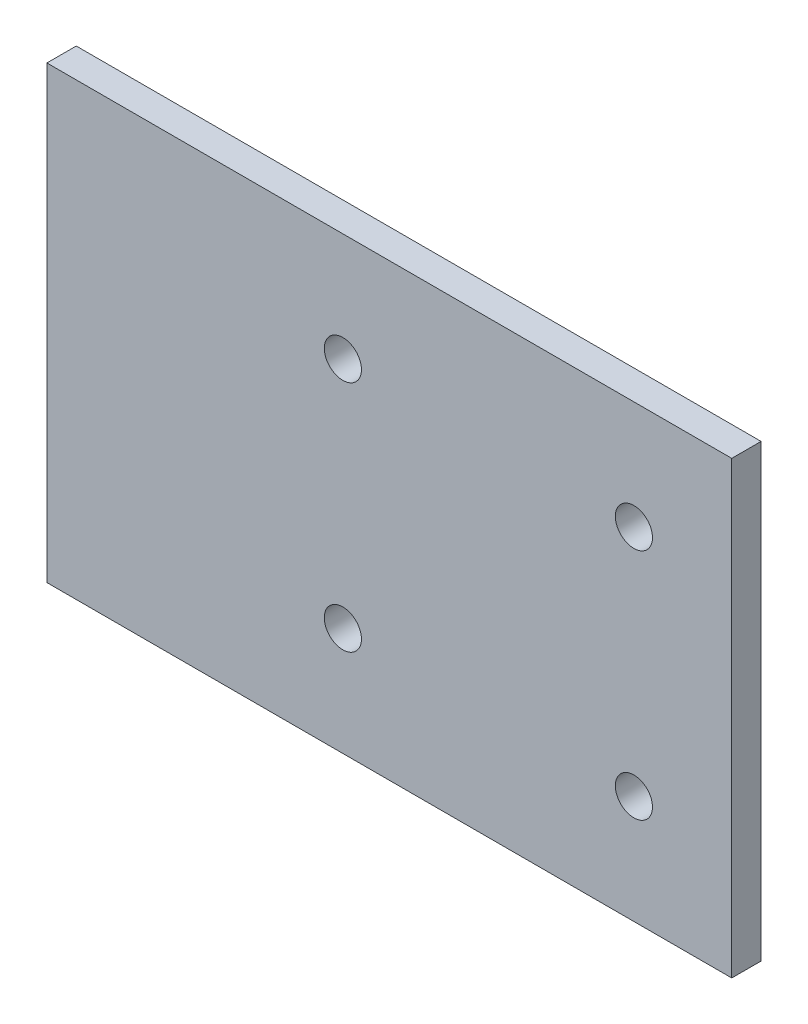
SolidWorks part; units mm, degrees
material "Oak"
ref_plane "Front Plane" through (0, 0, 0) normal (0, 0, 1) x (1, 0, 0)
ref_plane "Top Plane" through (0, 0, 0) normal (0, 1, 0) x (1, 0, 0)
ref_plane "Right Plane" through (0, 0, 0) normal (1, 0, 0) x (0, 0, -1)
sketch "Sketch1" plane through (0, 0, 0) normal (0, 0, 1) x (1, 0, 0)
  line L1 (-36.0143, 24.5902) -> (33.9857, 24.5902)
  line L2 (-36.0143, 24.5902) -> (-36.0143, -21.4098)
  line L3 (-36.0143, -21.4098) -> (33.9857, -21.4098)
  line L4 (33.9857, 24.5902) -> (33.9857, -21.4098)
  dimension "D1" = 46
  dimension "D2" = 70
extrude "Boss-Extrude1" add sketch "Sketch1" along normal blind 3
hole_wizard "#6 Clearance Hole1" positions "Sketch2" profile "Sketch3" hole size "#6" standard "ANSI Inch" end condition through all
sketch "Sketch2" plane through (0, 0, 3) normal (0, 0, 1) x (1, 0, 0)
  line L0 (33.9857, -21.4098) -> (33.9857, 24.5902) construction
  line L1 (33.9857, 24.5902) -> (-36.0143, 24.5902) construction
  line L2 (-36.0143, -21.4098) -> (33.9857, -21.4098) construction
  point P0 (23.9857, 13.5152)
  point P2 (23.9857, -10.3348)
  point P4 (-5.7643, -10.3348)
  point P6 (-5.7643, 13.5152)
  dimension "D1" = 29.75
  dimension "D2" = 29.75
  dimension "D3" = 23.85
  dimension "D4" = 23.85
  dimension "D5" = 10
  dimension "D6" = 11.075
  dimension "D7" = 10
  dimension "D8" = 11.075
sketch "Sketch3" plane through (23.9857, 13.5152, 3) normal (1, 0, 0) x (0, -1, 0)
  line L0 (0, 0) -> (0, 3)
  line L1 (0, 3) -> (1.8986, 3)
  line L2 (1.8986, 3) -> (1.8986, 0)
  line L5 (1.8986, 0) -> (0, 0)
  line L11 (0, -6.35) -> (0, 107.95) construction
  dimension "Thru Hole Dia." = 3.7973
  dimension "Thru Hole Depth" = 3
